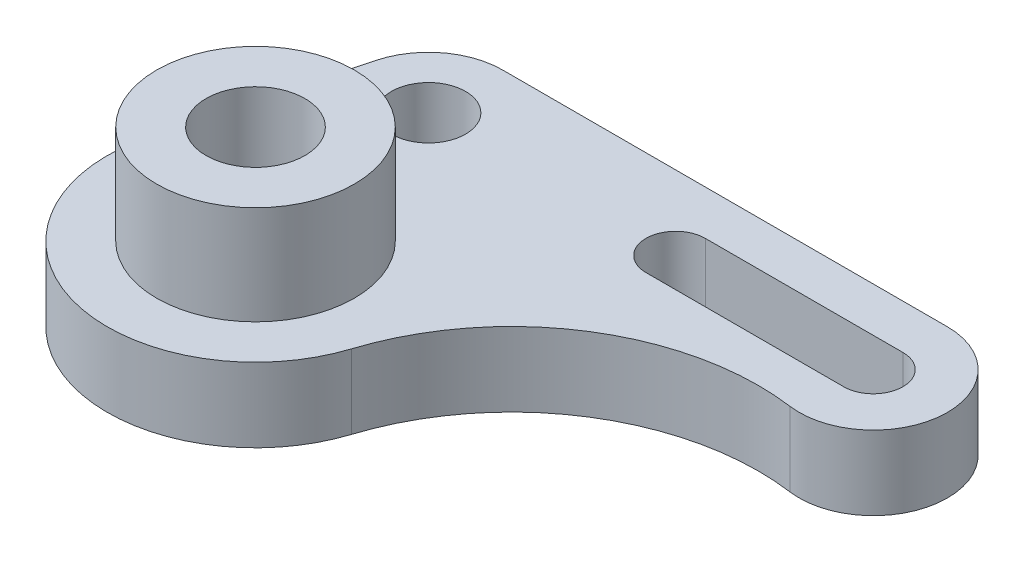
SolidWorks part; units mm, degrees
ref_plane "Front Plane" through (0, 0, 0) normal (0, 0, 1) x (1, 0, 0)
ref_plane "Top Plane" through (0, 0, 0) normal (0, 1, 0) x (1, 0, 0)
ref_plane "Right Plane" through (0, 0, 0) normal (1, 0, 0) x (0, 0, -1)
sketch "Sketch6" plane through (0, 0, 0) normal (0, 1, 0) x (1, 0, 0)
  line L0 (-45, 20) -> (5, 20) construction
  line L1 (5, 20) -> (45, 20) construction
  line L2 (-45, 20) -> (-45, -20) construction
  line L3 (-45, -20) -> (-40, -20) construction
sketch "Sketch1" plane through (0, 0, 0) normal (0, 1, 0) x (1, 0, 0)
  line L0 (-45, 20) -> (5, 20) construction
  line L1 (5, 20) -> (45, 20) construction
  line L2 (-45, 20) -> (-45, -20) construction
  line L3 (-45, -20) -> (-40, -20) construction
  line L4 (-59.5077, 23.8115) -> (-69.0153, -12.3769)
  line L5 (45, 35) -> (-45, 35)
  arc A0 (-45, 35) -> (-59.5077, 23.8115) centre (-45, 20) ccw
  arc A1 (42.9665, 5.1385) -> (45, 35) centre (45, 20) ccw
  arc A2 (-34.3282, 9.459) -> (-45, 9.5804) centre (-40, -20) ccw
  arc A3 (42.9665, 5.1385) -> (-11.4294, -29.15) centre (36.1882, -44.3999) ccw
  arc A4 (-69.0153, -12.3769) -> (-11.4294, -29.15) centre (-40, -20) ccw
  dimension "D1" = 30
  dimension "D4" = 30
  dimension "D7" = 60
  dimension "D8" = 50
  dimension "D2" = 50
  dimension "D3" = 40
  dimension "D5" = 40
  dimension "D6" = 5
extrude "Boss-Extrude1" add sketch "Sketch1" along normal blind 15
ref_plane "Plane1" through (0, 15, 0) normal (0, 1, 0) x (1, 0, 0)
sketch "Sketch7" plane through (0, 15, 0) normal (0, 1, 0) x (1, 0, 0)
  circle A0 centre (-40, -20) radius 20
  dimension "D1" = 40
extrude "Boss-Extrude2" add sketch "Sketch7" along normal blind 20
sketch "Sketch8" plane through (0, 15, 0) normal (0, 1, 0) x (1, 0, 0)
  line L0 (5, 26) -> (45, 26)
  line L1 (45, 14) -> (5, 14)
  circle A0 centre (-45, 20) radius 7.5
  arc A1 (5, 26) -> (5, 14) centre (5, 20) ccw
  arc A2 (45, 14) -> (45, 26) centre (45, 20) ccw
  dimension "D1" = 15
  dimension "D2" = 6
  dimension "D3" = 12
extrude "Cut-Extrude1" cut sketch "Sketch8" against normal blind 15
ref_plane "Plane2" through (0, 35, 0) normal (0, 1, 0) x (1, 0, 0)
sketch "Sketch9" plane through (0, 35, 0) normal (0, 1, 0) x (1, 0, 0)
  circle A0 centre (-40, -20) radius 10
  dimension "D1" = 20
extrude "Cut-Extrude2" cut sketch "Sketch9" against normal blind 35
